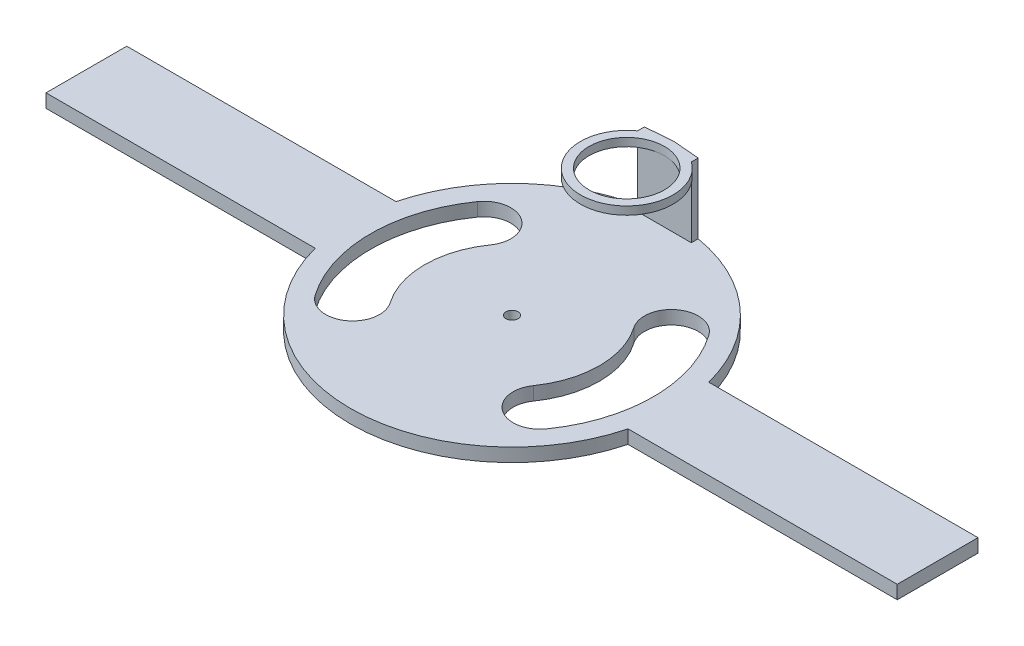
SolidWorks part; units mm, degrees
material "Custom Plastic"
ref_plane "Front Plane" through (0, 0, 0) normal (0, 0, 1) x (1, 0, 0)
ref_plane "Top Plane" through (0, 0, 0) normal (0, 1, 0) x (1, 0, 0)
ref_plane "Right Plane" through (0, 0, 0) normal (1, 0, 0) x (0, 0, -1)
sketch "Sketch1" plane through (0, 0, 0) normal (0, 1, 0) x (1, 0, 0)
  circle A0 centre (0, 0) radius 60
  dimension "D1" = 120
extrude "Boss-Extrude1" add sketch "Sketch1" along normal blind 5
sketch "Sketch2" plane through (0, 5, 0) normal (0, 1, 0) x (1, 0, 0)
  line L2 (0, 0) -> (34.814, 24.377) construction
  line L3 (-17.05, 0) -> (17.05, 0) construction
  line L4 (-26.6224, 18.6412) -> (-34.814, 24.377) construction
  line L5 (-26.6224, -18.6412) -> (-34.814, -24.377) construction
  line L6 (0, 0) -> (34.814, -24.377) construction
  arc A2 (-43.0055, 30.1128) -> (-43.0055, -30.1128) centre (0, 0) ccw
  arc A3 (-26.6224, 18.6412) -> (-26.6224, -18.6412) centre (0, 0) ccw
  arc A4 (-26.6224, 18.6412) -> (-43.0055, 30.1128) centre (-34.814, 24.377) ccw
  arc A5 (-43.0055, -30.1128) -> (-26.6224, -18.6412) centre (-34.814, -24.377) ccw
  arc A6 (43.0055, 30.1128) -> (26.6224, 18.6412) centre (34.814, 24.377) ccw
  arc A7 (26.6224, -18.6412) -> (43.0055, -30.1128) centre (34.814, -24.377) ccw
  arc A8 (26.6224, -18.6412) -> (26.6224, 18.6412) centre (0, 0) ccw
  arc A9 (43.0055, -30.1128) -> (43.0055, 30.1128) centre (0, 0) ccw
  dimension "D1" = 105
  dimension "D2" = 65
  dimension "D7" = 20
  dimension "D8" = 20
  dimension "D9" = 20
  dimension "D10" = 20
  dimension "D11" = 35
  dimension "D3" = 42.5
  dimension "D4" = 42.5
  dimension "D5" = 42.5
  dimension "D6" = 42.5
  dimension "D12" = 35
  dimension "D13" = 35
  dimension "D14" = 35
extrude "Cut-Extrude1" cut sketch "Sketch2" against normal blind 5
sketch "Sketch3" plane through (0, 5, 0) normal (0, 1, 0) x (1, 0, 0)
  line L0 (10, 56.6238) -> (10, 59.1608)
  line L2 (0, -17.05) -> (0, 17.05) construction
  line L3 (-10, 56.6238) -> (-10, 59.1608)
  line L4 (-10, 56.6238) -> (10, 56.6238)
  line L5 (-10, 0) -> (-10, 67.7783) construction
  line L6 (10, 0) -> (10, 67.7783) construction
  arc A0 (10, 59.1608) -> (-10, 59.1608) centre (0, 0) ccw
  dimension "D4" = 120
  dimension "D2" = 10
  dimension "D5" = 20
  dimension "D3" = 20
extrude "Boss-Extrude2" add sketch "Sketch3" along normal blind 23
sketch "Sketch4" plane through (0, 5, 0) normal (0, 1, 0) x (1, 0, 0)
  circle A0 centre (0, 0) radius 2.25
  dimension "D1" = 4.5
extrude "Cut-Extrude2" cut sketch "Sketch4" against normal blind 15
sketch "Sketch5" plane through (0, 5, 0) normal (0, 1, 0) x (1, 0, 0)
  line L0 (-58.0948, 15) -> (-158.0948, 15)
  line L2 (-58.0948, -15) -> (-158.0948, -15)
  line L3 (-158.0948, 15) -> (-158.0948, -15)
  arc A0 (-58.0948, 15) -> (-58.0948, -15) centre (0, 0) ccw
  dimension "D4" = 120
  dimension "D1" = 100
  dimension "D3" = 30
extrude "Boss-Extrude3" add sketch "Sketch5" against normal blind 5
mirror "Mirror1" about plane through (0, 0, 0) normal (1, 0, 0) of "Boss-Extrude3"
sketch "Sketch10" plane through (0, 28, 0) normal (0, 1, 0) x (1, 0, 0)
  line L0 (0, -17.05) -> (0, 17.05) construction
  line L1 (-10, 56.6238) -> (10, 56.6238) construction
  line L2 (-10, 59.1608) -> (-10, 56.6238)
  line L3 (-10, 59.1608) -> (0, 60)
  line L4 (0, 60) -> (10, 59.1608)
  line L5 (10, 59.1608) -> (10, 56.6238)
  line L6 (-10, 56.6238) -> (10, 56.6238) construction
  circle A0 centre (0, 42.6238) radius 14
  arc A1 (10, 59.1608) -> (-10, 59.1608) centre (0, 0) ccw construction
  arc A2 (-10, 56.6238) -> (10, 56.6238) centre (0, 42.6238) ccw
  line M2 (-10, 56.6238) -> (10, 56.6238)
  line M3 (10, 56.6238) -> (10, 59.1608)
  line M5 (-10, 59.1608) -> (-10, 56.6238)
  dimension "D1" = 28
  dimension "D2" = 14
extrude "Boss-Extrude6" add sketch "Sketch10" along normal blind 3 contours A2 A0 M2 | L4 L3 M5 M2 M3
